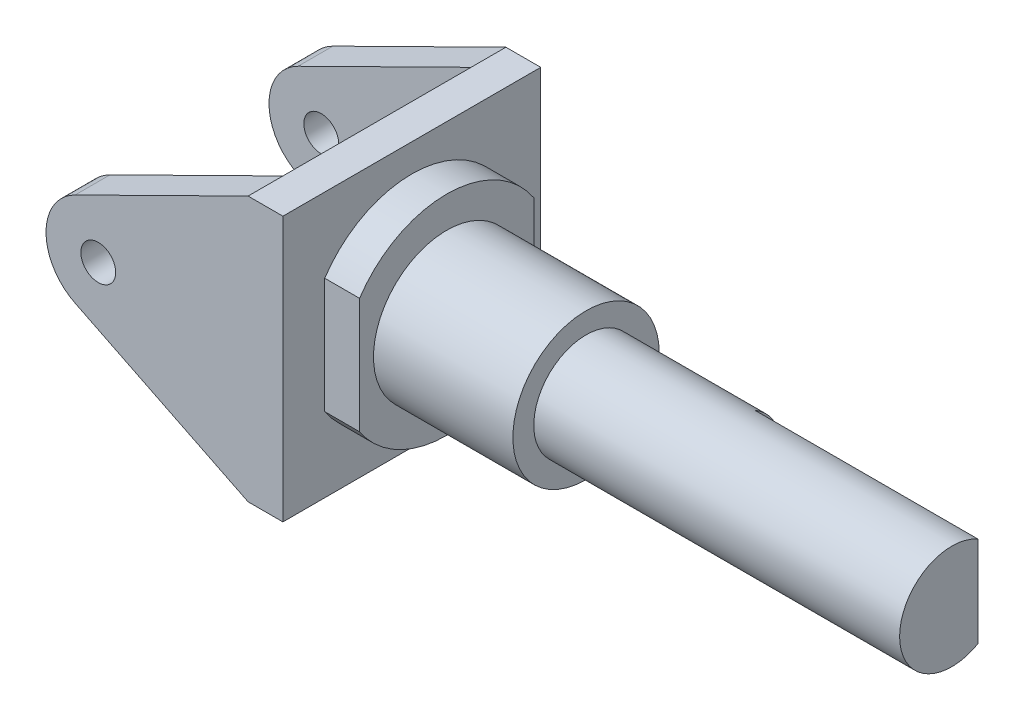
SolidWorks part; units mm, degrees
ref_plane "Front Plane" through (0, 0, 0) normal (0, 0, 1) x (1, 0, 0)
ref_plane "Top Plane" through (0, 0, 0) normal (0, 1, 0) x (1, 0, 0)
ref_plane "Right Plane" through (0, 0, 0) normal (1, 0, 0) x (0, 0, -1)
sketch "Sketch1" plane through (0, 0, 0) normal (0, 0, 1) x (1, 0, 0)
  line L0 (-77.5, 0) -> (-77.5, 30)
  line L1 (-77.5, 30) -> (-67.5, 30)
  line L2 (-67.5, 30) -> (-67.5, 21)
  line L3 (-67.5, 21) -> (-27.5, 21)
  line L4 (-27.5, 21) -> (-27.5, 15)
  line L5 (-27.5, 15) -> (77.5, 15)
  line L6 (77.5, 15) -> (77.5, 0)
  line L7 (77.5, 0) -> (-77.5, 0)
  line L8 (0, 0) -> (0, 120.5105) construction
  dimension "D1" = 105
  dimension "D2" = 40
  dimension "D3" = 10
  dimension "D4" = 30
  dimension "D5" = 21
  dimension "D6" = 15
revolve "Revolve1" add sketch "Sketch1" angle 360 about L7
sketch "Sketch2" plane through (-77.5, 0, 0) normal (-1, 0, 0) x (0, 0, 1)
  line L1 (-37, 38) -> (37, 38)
  line L2 (-37, 38) -> (-37, -38)
  line L3 (-37, -38) -> (37, -38)
  line L4 (37, 38) -> (37, -38)
  line L5 (-37, 38) -> (37, -38) construction
  line L6 (-37, -38) -> (37, 38) construction
  point P0 (0, 0)
  dimension "D1" = 74
  dimension "D2" = 76
extrude "Boss-Extrude1" add sketch "Sketch2" along normal blind 10
sketch "Sketch3" plane through (0, 0, -37) normal (0, 0, -1) x (-1, 0, 0)
  line L0 (87.5, 38) -> (87.5, -38) construction
  line L1 (87.5, 0) -> (87.5, -38)
  line L2 (87.5, 38) -> (137.1496, 13.4456)
  line L3 (87.5, -38) -> (137.1496, -13.4456)
  line L4 (77.5, 30) -> (77.5, -30) construction
  line L5 (0, 0) -> (199.0187, 0) construction
  line L6 (87.5, -38) -> (77.5, -38) construction
  line L7 (87.5, 38) -> (77.5, 38) construction
  line L8 (77.5, 38) -> (77.5, -38) construction
  line L9 (87.5, -38) -> (77.5, -38)
  line L10 (87.5, 38) -> (77.5, 38)
  line L11 (77.5, 38) -> (77.5, -38)
  arc A0 (137.1496, -13.4456) -> (137.1496, 13.4456) centre (130.5, 0) ccw
  circle A1 centre (130.5, 0) radius 5
  point P12 (0, 0)
  point P13 (0, 0)
  dimension "D1" = 30
  dimension "D2" = 10
  dimension "D3" = 53
extrude "Boss-Extrude2" add sketch "Sketch3" against normal blind 10 contours L3 A0 L2 L10 L11 L9
mirror "Mirror1" about plane through (0, 0, 0) normal (0, 0, 1) of "Boss-Extrude2"
hole_wizard "Hole1" positions "Sketch4" profile "Sketch5" legacy end condition through all
sketch "Sketch4" plane through (0, 0, -37) normal (0, 0, -1) x (-1, 0, 0)
  point P0 (130.5, 0)
sketch "Sketch5" plane through (-130.5, 0, -37) normal (1, 0, 0) x (0, 1, 0)
  line L0 (0, 0) -> (0, 74)
  line L1 (0, 74) -> (5, 74)
  line L2 (5, 74) -> (5, 0)
  line L3 (5, 0) -> (0, 0)
  line L4 (0, 110) -> (0, -10) construction
  dimension "Diameter" = 10
  dimension "Depth" = 74
sketch "Sketch8" plane through (77.5, 0, 0) normal (1, 0, 0) x (0, 0, -1)
  line L0 (25, 16.5831) -> (25, -16.5831)
  line L1 (-25, 16.5831) -> (-25, -16.5831)
  line L2 (0, 0) -> (0, 64.3265) construction
  circle A0 centre (0, 0) radius 30 construction
  arc A1 (-25, 16.5831) -> (-25, -16.5831) centre (0, 0) ccw
  arc A2 (25, -16.5831) -> (25, 16.5831) centre (0, 0) ccw
  dimension "D1" = 50
extrude "Cut-Extrude1" cut sketch "Sketch8" against normal blind 10 from offset 145 offset against normal yes
sketch "Sketch9" plane through (77.5, 0, 0) normal (1, 0, 0) x (0, 0, -1)
  line L0 (7.5, 12.9904) -> (7.5, -12.9904)
  circle A0 centre (0, 0) radius 15 construction
  arc A1 (7.5, -12.9904) -> (7.5, 12.9904) centre (0, 0) ccw
  dimension "D1" = 7.5
extrude "Cut-Extrude2" cut sketch "Sketch9" against normal blind 64
